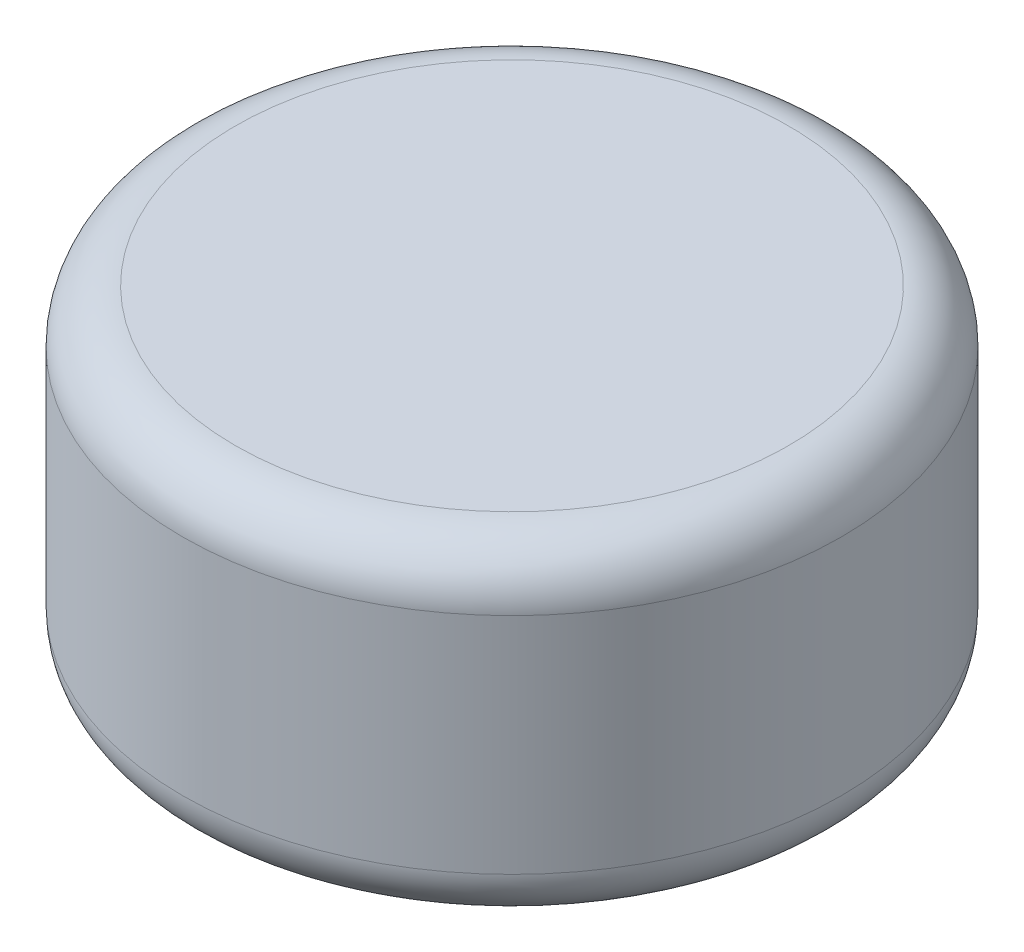
SolidWorks part; units mm, degrees
material "Vanadium"
ref_plane "Front Plane" through (0, 0, 0) normal (0, 0, 1) x (1, 0, 0)
ref_plane "Top Plane" through (0, 0, 0) normal (0, 1, 0) x (1, 0, 0)
ref_plane "Right Plane" through (0, 0, 0) normal (1, 0, 0) x (0, 0, -1)
sketch "Sketch1" plane through (0, 0, 0) normal (0, 1, 0) x (1, 0, 0)
  circle A0 centre (0, 0) radius 1.5875
  dimension "D1" = 3.175
extrude "Boss-Extrude1" add sketch "Sketch1" along normal blind 1.5875
fillet "Fillet1" radius 0.254 2 edges at (0, 0, 1.5875) (0, 1.5875, 1.5875)
